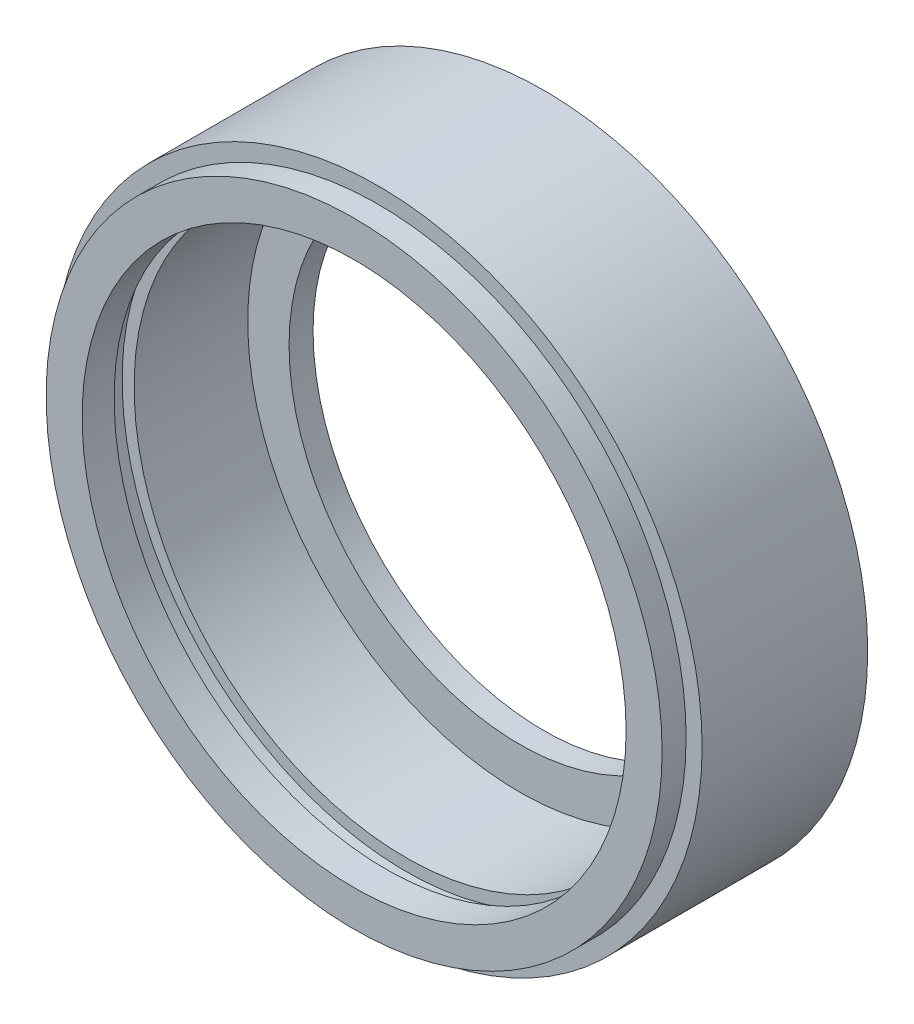
SolidWorks part; units mm, degrees
material "СТ3КП"
ref_plane "Спереди" through (0, 0, 0) normal (0, 0, 1) x (1, 0, 0)
ref_plane "Сверху" through (0, 0, 0) normal (0, 1, 0) x (1, 0, 0)
ref_plane "Справа" through (0, 0, 0) normal (1, 0, 0) x (0, 0, -1)
sketch "Эскиз1" plane through (0, 0, 0) normal (1, 0, 0) x (0, 0, -1)
  line L0 (0, 0) -> (0, 40.5) construction
  line L1 (-23.7, 0) -> (-23.7, 110) construction
  line L2 (-23.7, 38.5) -> (-20.7, 38.5) construction
  line L3 (-20.7, 38.5) -> (-20.7, 40.5) construction
  line L4 (-23.7, 40.5) -> (0, 40.5) construction
  line L5 (0, 28.8333) -> (0, 40.5)
  line L6 (-23.7, 34) -> (-23.7, 38.5)
  line L7 (-23.7, 38.5) -> (-20.7, 38.5)
  line L8 (-20.7, 38.5) -> (-20.7, 40.5)
  line L9 (-20.7, 40.5) -> (0, 40.5)
  line L10 (-23.7, 34) -> (-19.7, 34)
  line L11 (-3, 34) -> (-3, 28.8333)
  line L12 (-3, 28.8333) -> (0, 28.8333)
  line L13 (-4.5, 34) -> (-16.5, 34) construction
  line L14 (-3, -32.5) -> (-3, 32.5) construction
  line L15 (-19.7, 35.5) -> (-19.7, -34.3561) construction
  line L16 (-19.7, 35.5) -> (-19.7, 34)
  line L17 (-19.7, 35.5) -> (-17.2, 35.5)
  line L18 (-17.2, 35.5) -> (-17.2, 34)
  line L19 (-17.2, 34) -> (-3, 34)
  line L20 (-3, 28.8333) -> (-5.5, 28.8333) construction
  line L21 (-1010.5, 0) -> (48989.5, 0) construction
  dimension "D1" = 2.5
revolve "Повернуть1" add sketch "Эскиз1" angle 360 about L21
